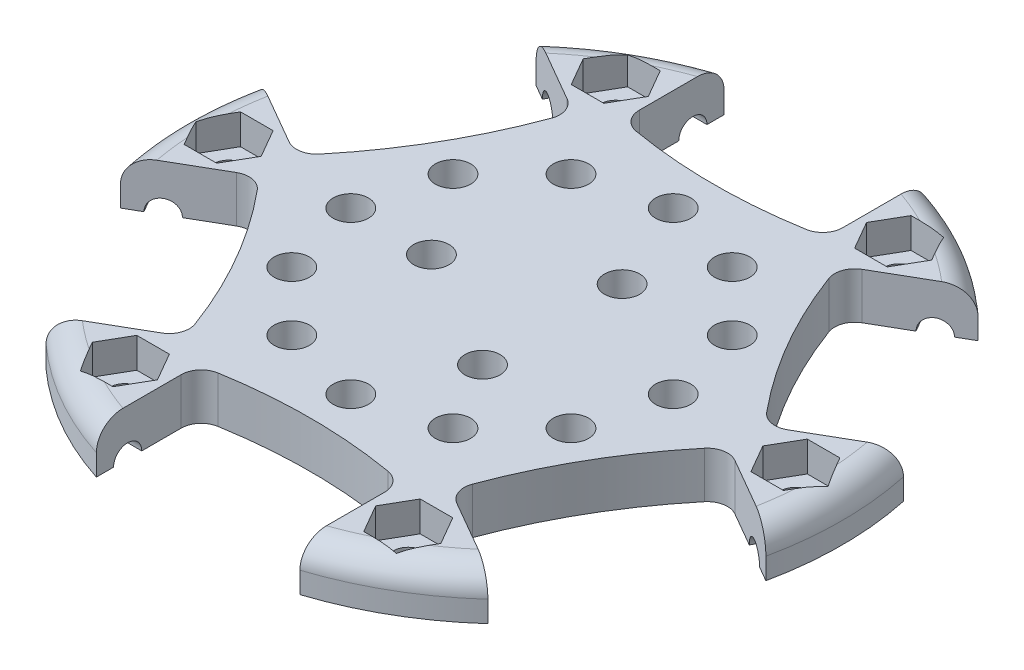
SolidWorks part; units mm, degrees
ref_plane "Plano frontal" through (0, 0, 0) normal (0, 0, 1) x (1, 0, 0)
ref_plane "Plano superior" through (0, 0, 0) normal (0, 1, 0) x (1, 0, 0)
ref_plane "Plano direito" through (0, 0, 0) normal (1, 0, 0) x (0, 0, -1)
sketch "Esboço1" plane through (0, 0, 0) normal (0, 0, 1) x (1, 0, 0)
  line L1 (-32.75, 2.1) -> (-32.75, 0)
  line L2 (-30.25, 4.6) -> (-6.07, 4.6)
  line L15 (-6.07, 4.6) -> (0, 4.6)
  line L17 (0, 0) -> (0, 4.6)
  line L18 (-32.75, 0) -> (0, 0)
  arc A3 (-30.25, 4.6) -> (-32.75, 2.1) centre (-30.25, 2.1) ccw
revolve "Revolução3" add sketch "Esboço1" angle 360 about L17
sketch "Esboço3" plane through (0, 0, 0) normal (0, -1, 0) x (1, 0, 0)
  line L2 (-10.1, 71.55) -> (10.1, 71.55)
  line L3 (-10.1, 71.55) -> (-10.1, 22.7384)
  line L4 (10.1, 71.55) -> (10.1, 22.7384)
  line L5 (10.1, -71.55) -> (-10.1, -71.55)
  line L6 (10.1, -71.55) -> (10.1, -22.7384)
  line L7 (-10.1, -71.55) -> (-10.1, -22.7384)
  line L10 (56.9141, 44.5219) -> (67.0141, 27.0281)
  line L11 (56.9141, 44.5219) -> (14.642, 20.116)
  line L12 (67.0141, 27.0281) -> (24.742, 2.6223)
  line L13 (-56.9141, -44.5219) -> (-67.0141, -27.0281)
  line L14 (-56.9141, -44.5219) -> (-14.642, -20.116)
  line L15 (-67.0141, -27.0281) -> (-24.742, -2.6223)
  line L18 (-67.0141, 27.0281) -> (-56.9141, 44.5219)
  line L19 (-67.0141, 27.0281) -> (-24.742, 2.6223)
  line L20 (-56.9141, 44.5219) -> (-14.642, 20.116)
  line L21 (67.0141, -27.0281) -> (56.9141, -44.5219)
  line L22 (67.0141, -27.0281) -> (24.742, -2.6223)
  line L23 (56.9141, -44.5219) -> (14.642, -20.116)
  arc A1 (-8.4375, 20.7671) -> (8.4375, 20.7671) centre (0, 70.05) ccw
  arc A2 (8.4375, 20.7671) -> (10.1, 22.7384) centre (8.1, 22.7384) ccw
  arc A3 (-8.4375, 20.7671) -> (-10.1, 22.7384) centre (-8.1, 22.7384) cw
  arc A4 (8.4375, -20.7671) -> (-8.4375, -20.7671) centre (0, -70.05) ccw
  arc A5 (-8.4375, -20.7671) -> (-10.1, -22.7384) centre (-8.1, -22.7384) ccw
  arc A6 (8.4375, -20.7671) -> (10.1, -22.7384) centre (8.1, -22.7384) cw
  arc A7 (13.766, 17.6906) -> (22.2035, 3.0764) centre (60.6651, 35.025) ccw
  arc A8 (22.2035, 3.0764) -> (24.742, 2.6223) centre (23.742, 4.3544) ccw
  arc A9 (13.766, 17.6906) -> (14.642, 20.116) centre (15.642, 18.384) cw
  arc A10 (-13.766, -17.6906) -> (-22.2035, -3.0764) centre (-60.6651, -35.025) ccw
  arc A11 (-22.2035, -3.0764) -> (-24.742, -2.6223) centre (-23.742, -4.3544) ccw
  arc A12 (-13.766, -17.6906) -> (-14.642, -20.116) centre (-15.642, -18.384) cw
  arc A13 (-22.2035, 3.0764) -> (-13.766, 17.6906) centre (-60.6651, 35.025) ccw
  arc A14 (-13.766, 17.6906) -> (-14.642, 20.116) centre (-15.642, 18.384) ccw
  arc A15 (-22.2035, 3.0764) -> (-24.742, 2.6223) centre (-23.742, 4.3544) cw
  arc A16 (22.2035, -3.0764) -> (13.766, -17.6906) centre (60.6651, -35.025) ccw
  arc A17 (13.766, -17.6906) -> (14.642, -20.116) centre (15.642, -18.384) ccw
  arc A18 (22.2035, -3.0764) -> (24.742, -2.6223) centre (23.742, -4.3544) cw
extrude "Corte-extrusão2" cut sketch "Esboço3" against normal blind 10
sketch "Esboço5" plane through (0, 0, 0) normal (0, -1, 0) x (1, 0, 0)
  line L0 (-12.6, 26.65) -> (12.6, 26.65)
  line L1 (-12.6, 28.05) -> (12.6, 28.05)
  line L10 (-12.6, 28.05) -> (-12.6, 26.65)
  line L13 (12.6, 28.05) -> (12.6, 26.65)
revolve "Corte-Revolução3" cut sketch "Esboço5" angle 360 about L1
sketch "Esboço6" plane through (0, 0, 0) normal (0, -1, 0) x (1, 0, 0)
  line L21 (-29.3796, 2.4131) -> (-16.7796, 24.2369)
  line L22 (-30.592, 3.1131) -> (-17.992, 24.9369)
  line L23 (-30.592, 3.1131) -> (-29.3796, 2.4131)
  line L24 (-17.992, 24.9369) -> (-16.7796, 24.2369)
revolve "Corte-Revolução4" cut sketch "Esboço6" angle 360 about L22
sketch "Esboço7" plane through (0, 0, 0) normal (0, -1, 0) x (1, 0, 0)
  line L9 (-16.7796, -24.2369) -> (-29.3796, -2.4131)
  line L10 (-17.992, -24.9369) -> (-30.592, -3.1131)
  line L11 (-17.992, -24.9369) -> (-16.7796, -24.2369)
  line L12 (-30.592, -3.1131) -> (-29.3796, -2.4131)
revolve "Corte-Revolução5" cut sketch "Esboço7" angle 360 about L10
sketch "Esboço8" plane through (0, 0, 0) normal (0, -1, 0) x (1, 0, 0)
  line L13 (16.7796, 24.2369) -> (29.3796, 2.4131)
  line L14 (17.992, 24.9369) -> (30.592, 3.1131)
  line L15 (17.992, 24.9369) -> (16.7796, 24.2369)
  line L16 (30.592, 3.1131) -> (29.3796, 2.4131)
revolve "Corte-Revolução6" cut sketch "Esboço8" angle 360 about L14
sketch "Esboço10" plane through (0, 0, 0) normal (0, -1, 0) x (1, 0, 0)
  line L1 (12.6, -26.65) -> (-12.6, -26.65)
  line L2 (12.6, -28.05) -> (-12.6, -28.05)
  line L3 (12.6, -28.05) -> (12.6, -26.65)
  line L4 (-12.6, -28.05) -> (-12.6, -26.65)
revolve "Corte-Revolução7" cut sketch "Esboço10" angle 360 about L2
sketch "Esboço11" plane through (0, 0, 0) normal (0, -1, 0) x (1, 0, 0)
  line L5 (29.3796, -2.4131) -> (16.7796, -24.2369)
  line L6 (30.592, -3.1131) -> (17.992, -24.9369)
  line L7 (30.592, -3.1131) -> (29.3796, -2.4131)
  line L8 (17.992, -24.9369) -> (16.7796, -24.2369)
revolve "Corte-Revolução8" cut sketch "Esboço11" angle 360 about L6
sketch "Esboço12" plane through (0, 0, 0) normal (0, -1, 0) x (1, 0, 0)
  circle A1 centre (0, 16) radius 1.75
  circle A2 centre (-8, 13.8564) radius 1.75
  circle A3 centre (-13.8564, 8) radius 1.75
  circle A4 centre (-16, 0) radius 1.75
  circle A5 centre (-13.8564, -8) radius 1.75
  circle A6 centre (-8, -13.8564) radius 1.75
  circle A7 centre (0, -16) radius 1.75
  circle A8 centre (8, -13.8564) radius 1.75
  circle A9 centre (13.8564, -8) radius 1.75
  circle A10 centre (16, 0) radius 1.75
  circle A11 centre (13.8564, 8) radius 1.75
  circle A12 centre (8, 13.8564) radius 1.75
  circle A13 centre (28.1296, 0) radius 1.3
  circle A14 centre (14.0648, 24.3609) radius 1.3
  circle A15 centre (-14.0648, 24.3609) radius 1.3
  circle A16 centre (-28.1296, 0) radius 1.3
  circle A18 centre (14.0648, -24.3609) radius 1.3
  circle A19 centre (-14.0648, -24.3609) radius 1.3
extrude "Corte-extrusão9" cut sketch "Esboço12" against normal through all
sketch "Esboço17" plane through (0, 0, 0) normal (0, -1, 0) x (1, 0, 0)
  circle A0 centre (4, 6.9282) radius 1.75
  circle A1 centre (-8, 0) radius 1.75
  circle A2 centre (4, -6.9282) radius 1.75
extrude "Corte-extrusão10" cut sketch "Esboço17" against normal through all
sketch "Esboço18" plane through (0, 4.6, 0) normal (0, 1, 0) x (1, 0, 0)
  line L1 (-31.0163, 0) -> (-29.573, -2.5)
  line L2 (-29.573, -2.5) -> (-26.6862, -2.5)
  line L3 (-26.6862, -2.5) -> (-25.2428, 0)
  line L4 (-25.2428, 0) -> (-26.6862, 2.5)
  line L5 (-26.6862, 2.5) -> (-29.573, 2.5)
  line L6 (-29.573, 2.5) -> (-31.0163, 0)
  line L8 (-15.5082, 26.8609) -> (-16.9515, 24.3609)
  line L9 (-16.9515, 24.3609) -> (-15.5082, 21.8609)
  line L10 (-15.5082, 21.8609) -> (-12.6214, 21.8609)
  line L11 (-12.6214, 21.8609) -> (-11.178, 24.3609)
  line L12 (-11.178, 24.3609) -> (-12.6214, 26.8609)
  line L13 (-12.6214, 26.8609) -> (-15.5082, 26.8609)
  line L15 (15.5082, 26.8609) -> (12.6214, 26.8609)
  line L16 (12.6214, 26.8609) -> (11.178, 24.3609)
  line L17 (11.178, 24.3609) -> (12.6214, 21.8609)
  line L18 (12.6214, 21.8609) -> (15.5082, 21.8609)
  line L19 (15.5082, 21.8609) -> (16.9515, 24.3609)
  line L20 (16.9515, 24.3609) -> (15.5082, 26.8609)
  line L22 (31.0163, 0) -> (29.573, 2.5)
  line L23 (29.573, 2.5) -> (26.6862, 2.5)
  line L24 (26.6862, 2.5) -> (25.2428, 0)
  line L25 (25.2428, 0) -> (26.6862, -2.5)
  line L26 (26.6862, -2.5) -> (29.573, -2.5)
  line L27 (29.573, -2.5) -> (31.0163, 0)
  line L29 (15.5082, -26.8609) -> (16.9515, -24.3609)
  line L30 (16.9515, -24.3609) -> (15.5082, -21.8609)
  line L31 (15.5082, -21.8609) -> (12.6214, -21.8609)
  line L32 (12.6214, -21.8609) -> (11.178, -24.3609)
  line L33 (11.178, -24.3609) -> (12.6214, -26.8609)
  line L34 (12.6214, -26.8609) -> (15.5082, -26.8609)
  line L36 (-15.5082, -26.8609) -> (-12.6214, -26.8609)
  line L37 (-12.6214, -26.8609) -> (-11.178, -24.3609)
  line L38 (-11.178, -24.3609) -> (-12.6214, -21.8609)
  line L39 (-12.6214, -21.8609) -> (-15.5082, -21.8609)
  line L40 (-15.5082, -21.8609) -> (-16.9515, -24.3609)
  line L41 (-16.9515, -24.3609) -> (-15.5082, -26.8609)
  circle A0 centre (-28.1296, 0) radius 2.5 construction
  circle A1 centre (-14.0648, 24.3609) radius 2.5 construction
  circle A2 centre (14.0648, 24.3609) radius 2.5 construction
  circle A3 centre (28.1296, 0) radius 2.5 construction
  circle A4 centre (14.0648, -24.3609) radius 2.5 construction
  circle A5 centre (-14.0648, -24.3609) radius 2.5 construction
extrude "Corte-extrusão12" cut sketch "Esboço18" against normal blind 3
sketch "Esboço19" plane through (0, 4.6, 0) normal (0, 1, 0) x (1, 0, 0)
  circle A0 centre (-14.0648, 24.3609) radius 1.5
  circle A1 centre (14.0648, 24.3609) radius 1.5
  circle A2 centre (14.0648, -24.3609) radius 1.5
  circle A3 centre (-14.0648, -24.3609) radius 1.5
  circle A4 centre (-28.1296, 0) radius 1.5
  circle A5 centre (28.1296, 0) radius 1.5
extrude "Corte-extrusão13" cut sketch "Esboço19" against normal through all
sketch "Esboço20" plane through (0, 4.6, 0) normal (0, 1, 0) x (1, 0, 0)
  line L0 (26.513, -2.8) -> (29.7462, -2.8)
  line L1 (-29.7462, 2.8) -> (-31.3627, 0)
  line L2 (-31.3627, 0) -> (-29.7462, -2.8)
  line L3 (-29.7462, -2.8) -> (-26.513, -2.8)
  line L4 (-26.513, -2.8) -> (-24.8964, 0)
  line L5 (-24.8964, 0) -> (-26.513, 2.8)
  line L6 (-26.513, 2.8) -> (-29.7462, 2.8)
  line L7 (29.7462, -2.8) -> (31.3627, 0)
  line L8 (29.7462, 2.8) -> (26.513, 2.8)
  line L9 (24.8964, 0) -> (26.513, -2.8)
  line L10 (26.513, 2.8) -> (24.8964, 0)
  line L11 (31.3627, 0) -> (29.7462, 2.8)
  line L12 (15.6814, 27.1609) -> (12.4482, 27.1609)
  line L13 (10.8316, 24.3609) -> (12.4482, 21.5609)
  line L14 (17.298, 24.3609) -> (15.6814, 27.1609)
  line L15 (12.4482, 27.1609) -> (10.8316, 24.3609)
  line L16 (15.6814, 21.5609) -> (17.298, 24.3609)
  line L17 (12.4482, 21.5609) -> (15.6814, 21.5609)
  line L18 (-10.8316, 24.3609) -> (-12.4482, 27.1609)
  line L19 (-12.4482, 21.5609) -> (-10.8316, 24.3609)
  line L20 (-12.4482, 27.1609) -> (-15.6814, 27.1609)
  line L21 (-17.298, 24.3609) -> (-15.6814, 21.5609)
  line L22 (-15.6814, 27.1609) -> (-17.298, 24.3609)
  line L23 (-15.6814, 21.5609) -> (-12.4482, 21.5609)
  line L24 (-15.6814, -27.1609) -> (-12.4482, -27.1609)
  line L25 (-12.4482, -27.1609) -> (-10.8316, -24.3609)
  line L26 (-15.6814, -21.5609) -> (-17.298, -24.3609)
  line L27 (17.298, -24.3609) -> (15.6814, -21.5609)
  line L28 (-12.4482, -21.5609) -> (-15.6814, -21.5609)
  line L29 (15.6814, -27.1609) -> (17.298, -24.3609)
  line L30 (12.4482, -21.5609) -> (10.8316, -24.3609)
  line L31 (10.8316, -24.3609) -> (12.4482, -27.1609)
  line L32 (-17.298, -24.3609) -> (-15.6814, -27.1609)
  line L33 (15.6814, -21.5609) -> (12.4482, -21.5609)
  line L34 (12.4482, -27.1609) -> (15.6814, -27.1609)
  line L35 (-10.8316, -24.3609) -> (-12.4482, -21.5609)
  circle A0 centre (-28.1296, 0) radius 2.8 construction
  circle A1 centre (28.1296, 0) radius 2.8 construction
  circle A2 centre (14.0648, 24.3609) radius 2.8 construction
  circle A3 centre (-14.0648, 24.3609) radius 2.8 construction
  circle A4 centre (14.0648, -24.3609) radius 2.8 construction
  circle A5 centre (-14.0648, -24.3609) radius 2.8 construction
extrude "Corte-extrusão14" cut sketch "Esboço20" against normal blind 3
